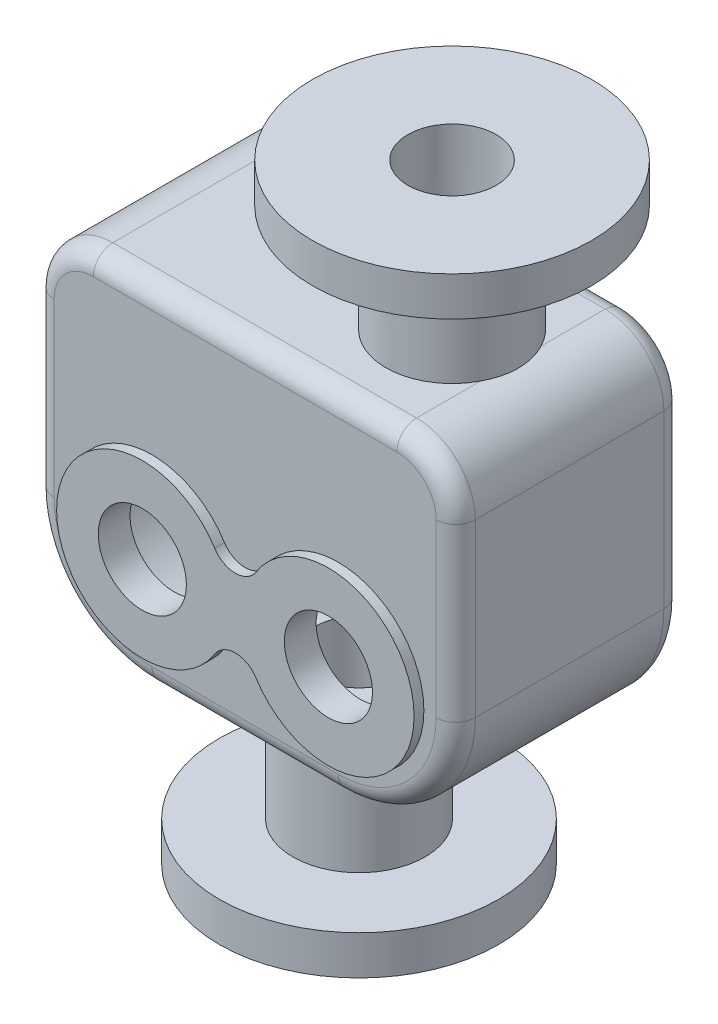
SolidWorks part; units mm, degrees
ref_plane "前基準面" through (0, 0, 0) normal (0, 0, 1) x (1, 0, 0)
ref_plane "上基準面" through (0, 0, 0) normal (0, 1, 0) x (1, 0, 0)
ref_plane "右基準面" through (0, 0, 0) normal (1, 0, 0) x (0, 0, -1)
sketch "草圖1" plane through (0, 0, 0) normal (0, 0, 1) x (1, 0, 0)
  line L0 (0, 0) -> (0, 152.9013) construction
  line L1 (-38, 0) -> (38, 0)
  line L2 (86, 48) -> (86, 118)
  line L3 (62, 142) -> (-62, 142)
  line L4 (-86, 48) -> (-86, 118)
  arc A0 (38, 0) -> (86, 48) centre (38, 48) ccw
  arc A1 (86, 118) -> (62, 142) centre (62, 118) ccw
  arc A2 (-86, 118) -> (-62, 142) centre (-62, 118) cw
  arc A3 (-38, 0) -> (-86, 48) centre (-38, 48) cw
  point P16 (0, 142)
  dimension "D1" = 48
  dimension "D2" = 24
  dimension "D3" = 94
  dimension "D4" = 172
extrude "伸長1" add sketch "草圖1" along normal mid plane 93
fillet "圓角1" radius 8 16 edges at (78.9706, 134.9706, 46.5) (86, 83, 46.5) (71.9411, 14.0589, 46.5) (0, 0, 46.5) (-71.9411, 14.0589, 46.5) (-86, 83, 46.5) (-78.9706, 134.9706, 46.5) (78.9706, 134.9706, -46.5) (86, 83, -46.5) (71.9411, 14.0589, -46.5) (0, 0, -46.5) (-71.9411, 14.0589, -46.5) (-86, 83, -46.5) (-78.9706, 134.9706, -46.5) (0, 142, 46.5) (0, 142, -46.5)
shell "薄殼1" thickness 9
fillet "圓角2" radius 3 16 edges at (0, 9, 37.5) (65.5772, 20.4228, 37.5) (77, 83, 37.5) (72.6066, 128.6066, 37.5) (0, 133, 37.5) (-72.6066, 128.6066, 37.5) (-77, 83, 37.5) (0, 9, -37.5) (65.5772, 20.4228, -37.5) (77, 83, -37.5) (72.6066, 128.6066, -37.5) (0, 133, -37.5) (-72.6066, 128.6066, -37.5) (-77, 83, -37.5) (-65.5772, 20.4228, 37.5) (-65.5772, 20.4228, -37.5)
sketch "草圖2" plane through (0, 0, 46.5) normal (0, 0, 1) x (1, 0, 0)
  line L0 (0, 0) -> (0, 98.806) construction
  arc A0 (8.4444, 29.2525) -> (8.4444, 66.7475) centre (38, 48) ccw
  arc A1 (38, 0) -> (86, 48) centre (38, 48) ccw construction
  arc A2 (-8.4444, 29.2525) -> (-8.4444, 66.7475) centre (-38, 48) cw
  arc A3 (-8.4444, 66.7475) -> (8.4444, 66.7475) centre (0, 72.1039) ccw
  arc A4 (8.4444, 29.2525) -> (-8.4444, 29.2525) centre (0, 23.8961) ccw
  dimension "D1" = 70
  dimension "D2" = 10
extrude "伸長2" add sketch "草圖2" along normal blind 4
sketch "草圖3" plane through (0, 0, 50.5) normal (0, 0, 1) x (1, 0, 0)
  circle A0 centre (38, 48) radius 18
  circle A1 centre (-38, 48) radius 18
  dimension "D1" = 36
extrude "除料-伸長1" cut sketch "草圖3" against normal up to next
sketch "草圖4" plane through (0, 0, -46.5) normal (0, 0, -1) x (-1, 0, 0)
  circle A0 centre (-38, 48) radius 27.5
  circle A1 centre (38, 48) radius 27.5
  dimension "D1" = 55
extrude "除料-伸長2" cut sketch "草圖4" against normal up to next
sketch "草圖5" plane through (0, 0, 0) normal (0, 0, 1) x (1, 0, 0)
  line L0 (0, 0) -> (0, -78.7491) construction
  line L1 (0, -66) -> (57, -66)
  line L2 (57, -66) -> (57, -50)
  line L3 (57, -50) -> (27, -50)
  line L4 (27, -50) -> (27, 0)
  line L5 (38, 0) -> (-38, 0) construction
  line L6 (27, 0) -> (0, 0)
  line L7 (0, 0) -> (0, -66)
  circle A0 centre (38, 48) radius 18 construction
  dimension "D1" = 16
  dimension "D2" = 114
  dimension "D3" = 54
  dimension "D4" = 114
revolve "旋轉1" add sketch "草圖5" angle 360 about L0
sketch "草圖6" plane through (0, 0, 0) normal (0, 0, 1) x (1, 0, 0)
  line L0 (38, 124.7535) -> (38, 229.4053) construction
  line L1 (11, 133) -> (11, 186)
  line L2 (62, 133) -> (-62, 133) construction
  line L3 (11, 186) -> (-19, 186)
  line L4 (-19, 186) -> (-19, 202)
  line L5 (-19, 202) -> (38, 202)
  line L6 (38, 202) -> (38, 133)
  line L7 (38, 133) -> (11, 133)
  line L8 (-57, -66) -> (57, -66) construction
  dimension "D1" = 54
  dimension "D2" = 114
  dimension "D3" = 16
  dimension "D4" = 268
  dimension "D5" = 38
revolve "旋轉2" add sketch "草圖6" angle 360 about L0
sketch "草圖7" plane through (0, -66, 0) normal (0, -1, 0) x (1, 0, 0)
  circle A0 centre (0, 0) radius 18
  dimension "D1" = 36
extrude "除料-伸長3" cut sketch "草圖7" against normal up to next
sketch "草圖8" plane through (0, 202, 0) normal (0, 1, 0) x (-1, 0, 0)
  circle A0 centre (-38, 0) radius 18
  dimension "D1" = 36
extrude "除料-伸長4" cut sketch "草圖8" against normal up to next
